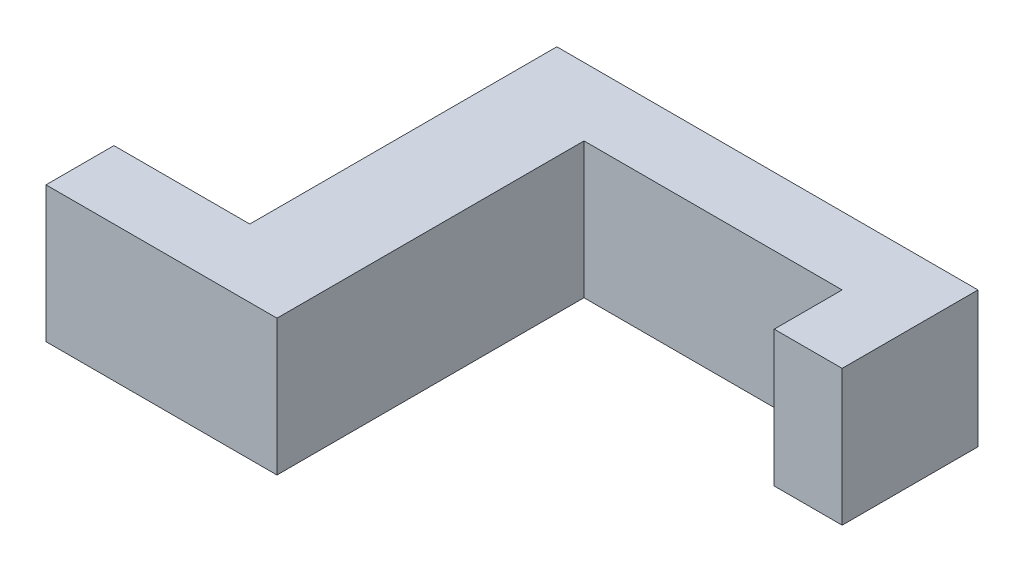
SolidWorks part; units mm, degrees
ref_plane "Front Plane" through (0, 0, 0) normal (0, 0, 1) x (1, 0, 0)
ref_plane "Top Plane" through (0, 0, 0) normal (0, 1, 0) x (1, 0, 0)
ref_plane "Right Plane" through (0, 0, 0) normal (1, 0, 0) x (0, 0, -1)
sketch "Sketch1" plane through (0, 0, 0) normal (0, 1, 0) x (1, 0, 0)
  line L1 (7, 17.6) -> (26, 17.6)
  line L2 (26, 17.6) -> (26, 12.6)
  line L3 (26, 12.6) -> (31, 12.6)
  line L4 (31, 12.6) -> (31, 22.6)
  line L5 (31, 22.6) -> (0, 22.6)
  line L6 (0, 22.6) -> (0, 0)
  line L7 (0, 0) -> (-10, 0)
  line L8 (-10, 0) -> (-10, -5)
  line L9 (-10, -5) -> (7, -5)
  line L11 (7, 17.6) -> (7, -5)
  point P0 (7, 6.3)
  point P8 (0, 0)
  dimension "D1" = 22.6
  dimension "D2" = 10
  dimension "D3" = 5
  dimension "D4" = 17
  dimension "D5" = 7
  dimension "D6" = 19
  dimension "D7" = 5
  dimension "D8" = 5
  dimension "D9" = 10
  dimension "D10" = 22.6
extrude "Boss-Extrude1" add sketch "Sketch1" along normal blind 10
